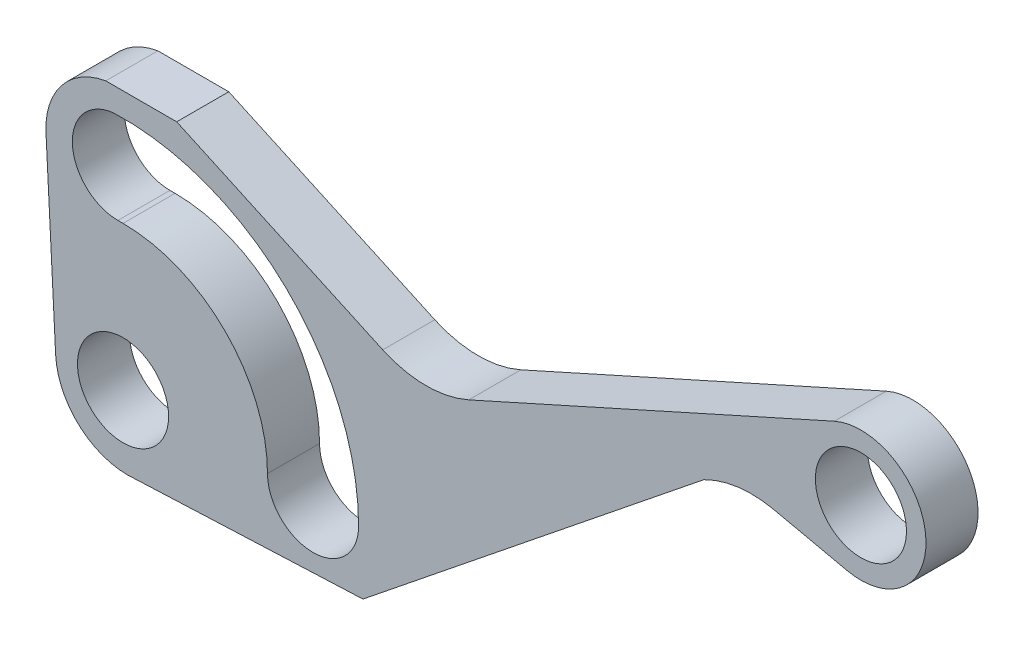
SolidWorks part; units mm, degrees
ref_plane "Front Plane" through (0, 0, 0) normal (0, 0, 1) x (1, 0, 0)
ref_plane "Top Plane" through (0, 0, 0) normal (0, 1, 0) x (1, 0, 0)
ref_plane "Right Plane" through (0, 0, 0) normal (1, 0, 0) x (0, 0, -1)
sketch "Sketch2" plane through (0, 0, 0) normal (0, 0, 1) x (1, 0, 0)
  line L0 (13.45, 15.25) -> (13.45, 6.55) construction
  line L1 (6.45, 15.25) -> (13.45, 15.25) construction
  line L2 (6.45, 15.25) -> (6.45, 6.4403) construction
  line L3 (9.9551, -1.75) -> (13.45, -1.75) construction
  line L4 (13.45, 15.25) -> (13.45, -1.75) construction
  line L5 (13.45, 6.55) -> (23.95, 6.55) construction
  line L6 (-2.9597, 7.0942) -> (-2.5895, -0.1124)
  line L7 (22.318, 8.1815) -> (9.2184, -2.3418)
  line L8 (23.95, 6.55) -> (28.35, 6.55) construction
  line L9 (28.35, 6.55) -> (28.35, 10.35) construction
  line L10 (27.811, 7.9088) -> (25.0059, 8.5282)
  line L11 (9.2184, -2.3418) -> (0.1706, -2.7344)
  line L12 (13.2851, 6.3203) -> (27.3252, 12.6303)
  line L13 (-0.1971, 5.55) -> (0, 5.55)
  line L14 (9.9788, 6.3325) -> (2.0624, 9.9607)
  line L15 (-0.6627, 9.9607) -> (2.0624, 9.9607)
  circle A0 centre (0, 0) radius 1.75
  arc A1 (-0.3574, 9.0426) -> (-0.1971, 5.55) centre (-0.1971, 7.3) ccw
  circle A2 centre (23.95, 6.55) radius 1.875 construction
  arc A3 (5.55, 0) -> (9.0496, 0.0357) centre (7.3, 0) ccw
  arc A4 (5.55, 0) -> (0, 5.55) centre (0, 0) ccw
  circle A7 centre (28.35, 10.35) radius 1.75
  arc A8 (27.811, 7.9088) -> (27.3252, 12.6303) centre (28.35, 10.35) ccw
  arc A9 (9.9788, 6.3325) -> (13.2851, 6.3203) centre (11.6454, 9.9688) ccw
  arc A10 (25.0059, 8.5282) -> (22.318, 8.1815) centre (24.1434, 4.6223) ccw
  arc A11 (9.0496, 0.0357) -> (-0.3574, 9.0426) centre (0, 0) ccw
  arc A14 (-2.5895, -0.1124) -> (0.1706, -2.7344) centre (0.1706, 0.0294) ccw
  arc A15 (-2.9597, 7.0942) -> (-0.6627, 9.9607) centre (-0.1996, 7.236) cw
  dimension "D1" = 3.5
  dimension "D2" = 7.3
  dimension "D4" = 3.5
  dimension "D5" = 3.5
  dimension "D6" = 17
  dimension "D7" = 6.45
  dimension "D8" = 1.75
  dimension "D11" = 3.75
  dimension "D9" = 8.7
  dimension "D17" = 3.5
  dimension "D18" = 5
  dimension "D19" = 4
  dimension "D3" = 7.3
  dimension "D10" = 10.5
  dimension "D15" = 4.4
  dimension "D16" = 3.8
extrude "Boss-Extrude1" add sketch "Sketch2" along normal blind 2
scale "Scale1" scale about centroid uniform scaling yes scale factor 2
